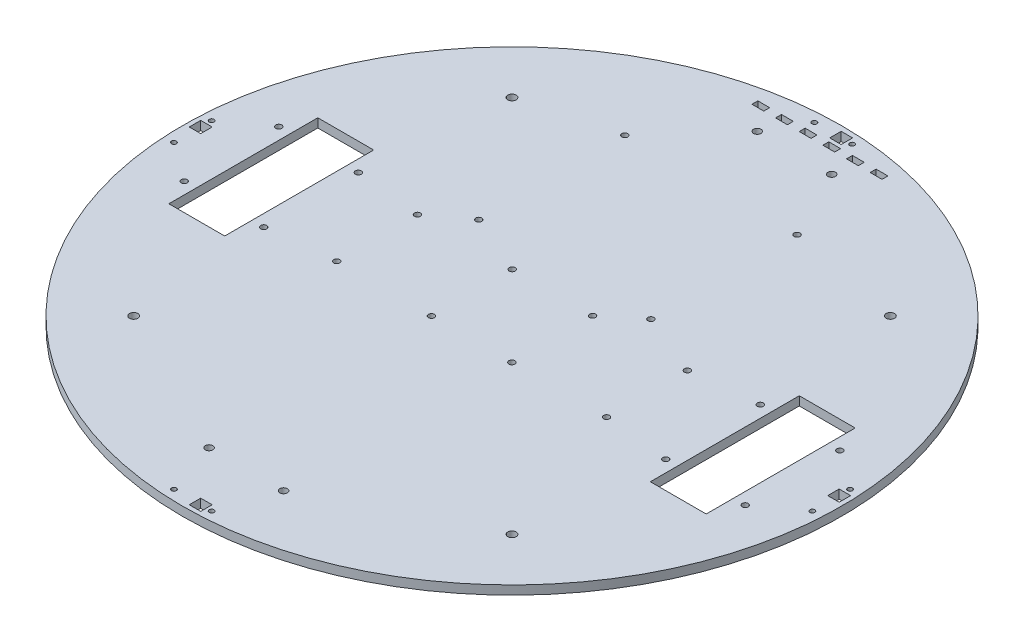
SolidWorks part; units mm, degrees
ref_plane "Front Plane" through (0, 0, 0) normal (0, 0, 1) x (1, 0, 0)
ref_plane "Top Plane" through (0, 0, 0) normal (0, 1, 0) x (1, 0, 0)
ref_plane "Right Plane" through (0, 0, 0) normal (1, 0, 0) x (0, 0, -1)
sketch "Sketch1" plane through (0, 0, 0) normal (0, 1, 0) x (1, 0, 0)
  line L0 (168.375, 7.335) -> (174.525, 7.335)
  line L1 (-144.3, 40) -> (-114.3, 40)
  line L2 (-144.3, 40) -> (-144.3, -40)
  line L3 (-144.3, -40) -> (-114.3, -40)
  line L4 (-114.3, 40) -> (-114.3, -40)
  line L13 (114.3, 40) -> (144.3, 40)
  line L14 (114.3, 40) -> (114.3, -40)
  line L15 (114.3, -40) -> (144.3, -40)
  line L16 (144.3, 40) -> (144.3, -40)
  line L17 (1.185, -168.375) -> (7.335, -168.375)
  line L18 (1.185, -168.375) -> (1.185, -174.525)
  line L19 (1.185, -174.525) -> (7.335, -174.525)
  line L20 (7.335, -168.375) -> (7.335, -174.525)
  line L21 (168.375, 7.335) -> (168.375, 1.185)
  line L22 (168.375, 1.185) -> (174.525, 1.185)
  line L23 (174.525, 7.335) -> (174.525, 1.185)
  line L24 (-174.525, 7.335) -> (-168.375, 7.335)
  line L25 (-174.525, 7.335) -> (-174.525, 1.185)
  line L26 (-174.525, 1.185) -> (-168.375, 1.185)
  line L27 (-168.375, 7.335) -> (-168.375, 1.185)
  line L28 (-21.295, 162.8645) -> (-14.945, 162.8645)
  line L29 (-33.995, 166.0395) -> (-27.645, 166.0395)
  line L30 (-33.995, 166.0395) -> (-33.995, 162.8645)
  line L31 (-33.995, 162.8645) -> (-27.645, 162.8645)
  line L32 (-27.645, 166.0395) -> (-27.645, 162.8645)
  line L33 (-14.945, 166.0395) -> (-14.945, 162.8645)
  line L34 (-21.295, 166.0395) -> (-14.945, 166.0395)
  line L35 (-21.295, 166.0395) -> (-21.295, 162.8645)
  line L36 (-8.595, 162.8645) -> (-2.245, 162.8645)
  line L37 (-2.245, 166.0395) -> (-2.245, 162.8645)
  line L38 (-8.595, 166.0395) -> (-2.245, 166.0395)
  line L39 (-8.595, 166.0395) -> (-8.595, 162.8645)
  line L40 (4.105, 162.8645) -> (10.455, 162.8645)
  line L41 (10.455, 166.0395) -> (10.455, 162.8645)
  line L42 (4.105, 166.0395) -> (10.455, 166.0395)
  line L43 (4.105, 166.0395) -> (4.105, 162.8645)
  line L44 (16.805, 162.8645) -> (23.155, 162.8645)
  line L45 (23.155, 166.0395) -> (23.155, 162.8645)
  line L46 (16.805, 166.0395) -> (23.155, 166.0395)
  line L47 (16.805, 166.0395) -> (16.805, 162.8645)
  line L48 (29.505, 162.8645) -> (35.855, 162.8645)
  line L49 (35.855, 166.0395) -> (35.855, 162.8645)
  line L50 (29.505, 166.0395) -> (35.855, 166.0395)
  line L51 (29.505, 166.0395) -> (29.505, 162.8645)
  circle A0 centre (0, 0) radius 177
  circle A1 centre (-150.65, 25.4) radius 1.6
  circle A2 centre (-150.65, -25.4) radius 1.6
  circle A3 centre (150.65, 25.4) radius 1.6
  circle A4 centre (150.65, -25.4) radius 1.6
  circle A5 centre (-107.95, 25.4) radius 1.6
  circle A6 centre (-107.95, -25.4) radius 1.6
  circle A7 centre (107.95, 25.4) radius 1.6
  circle A8 centre (107.95, -25.4) radius 1.6
  circle A9 centre (-53.7, 114.3) radius 1.6
  circle A10 centre (38.8, 114.3) radius 1.6
  circle A11 centre (-53.7, 35.8) radius 1.6
  circle A12 centre (38.8, 35.8) radius 1.6
  circle A13 centre (-101.6, -101.6) radius 2.2479
  circle A14 centre (101.6, -101.6) radius 2.2479
  circle A15 centre (-101.6, 101.6) radius 2.2479
  circle A16 centre (101.6, 101.6) radius 2.2479
  circle A17 centre (-20, -142.687) radius 2
  circle A18 centre (20, -142.687) radius 2
  circle A19 centre (-20, 151.7193) radius 2
  circle A20 centre (20, 151.7193) radius 2
  circle A21 centre (-10.125, -171.45) radius 1.3
  circle A22 centre (10.125, -171.45) radius 1.3
  circle A23 centre (171.45, -10.125) radius 1.3
  circle A24 centre (171.45, 10.125) radius 1.3
  circle A25 centre (-171.45, -10.125) radius 1.3
  circle A26 centre (-171.45, 10.125) radius 1.3
  point P9 (-114.3, 0)
  point P10 (-0.9618, 0)
  point P11 (-0.9618, 0)
  point P14 (114.3, 0)
  point P26 (-144.3, 0)
  point P27 (144.3, 0)
  dimension "D1" = 354
  dimension "D10" = 3.2
  dimension "D12" = 6.35
  dimension "D13" = 3.2
  dimension "D16" = 6.35
  dimension "D17" = 50.8
  dimension "D20" = 3.2
  dimension "D22" = 3.2
  dimension "D23" = 6.35
  dimension "D24" = 50.8
  dimension "D25" = 25.4
  dimension "D26" = 3.2
  dimension "D27" = 3.2
  dimension "D32" = 3.2
  dimension "D33" = 3.2
  dimension "D34" = 3.2
  dimension "D35" = 3.2
  dimension "D44" = 4.4958
  dimension "D45" = 4.4958
  dimension "D46" = 4.4958
  dimension "D47" = 4.4958
  dimension "D55" = 4
  dimension "D56" = 4
  dimension "D59" = 20
  dimension "D60" = 4
  dimension "D61" = 4
  dimension "D62" = 0
  dimension "D63" = 40
  dimension "D64" = 20
  dimension "D65" = 2.6
  dimension "D66" = 2.6
  dimension "D74" = 171.45
  dimension "D75" = 2.6
  dimension "D76" = 2.6
  dimension "D77" = 0
  dimension "D87" = 2.6
  dimension "D88" = 2.6
  dimension "D90" = 2.79
  dimension "D92" = 0
  dimension "D122" = 3.2
  dimension "D123" = 3.2
  dimension "D2" = 30
  dimension "D3" = 80
  dimension "D4" = 0
  dimension "D5" = 114.3
  dimension "D6" = 30
  dimension "D7" = 80
  dimension "D8" = 0
  dimension "D9" = 114.3
  dimension "D11" = 50.8
  dimension "D14" = 6.35
  dimension "D15" = 25.4
  dimension "D18" = 25.4
  dimension "D19" = 6.35
  dimension "D21" = 6.35
  dimension "D28" = 50.8
  dimension "D29" = 6.35
  dimension "D30" = 6.35
  dimension "D31" = 25.4
  dimension "D36" = 78.5
  dimension "D37" = 78.5
  dimension "D38" = 92.5
  dimension "D39" = 92.5
  dimension "D40" = 0
  dimension "D41" = 0
  dimension "D42" = 38.8
  dimension "D43" = 114.3
  dimension "D48" = 203.2
  dimension "D49" = 203.2
  dimension "D50" = 203.2
  dimension "D51" = 203.2
  dimension "D52" = 0
  dimension "D53" = 101.6
  dimension "D54" = 101.6
  dimension "D57" = 40
  dimension "D58" = 0
  dimension "D67" = 0
  dimension "D68" = 20.25
  dimension "D69" = 10.125
  dimension "D70" = 6.15
  dimension "D71" = 6.15
  dimension "D72" = 2.79
  dimension "D73" = 3.075
  dimension "D78" = 20.25
  dimension "D79" = 10.125
  dimension "D80" = 6.15
  dimension "D81" = 6.15
  dimension "D82" = 2.79
  dimension "D83" = 3.075
  dimension "D84" = 171.45
  dimension "D85" = 6.15
  dimension "D86" = 6.15
  dimension "D89" = 20.25
  dimension "D91" = 3.075
  dimension "D93" = 171.45
  dimension "D94" = 10.125
  dimension "D95" = 3.175
  dimension "D96" = 6.35
  dimension "D97" = 6
extrude "Boss-Extrude1" add sketch "Sketch1" along normal blind 4.7625
sketch "Sketch2" plane through (0, 4.7625, 0) normal (0, 1, 0) x (1, 0, 0)
  circle A4 centre (21.59, 21.69) radius 1.6
  circle A5 centre (21.59, -21.69) radius 1.6
  circle A6 centre (72.47, -21.69) radius 1.6
  circle A7 centre (72.47, 21.69) radius 1.6
  circle A12 centre (-72.47, 21.69) radius 1.6
  circle A13 centre (-72.47, -21.69) radius 1.6
  circle A14 centre (-21.59, -21.69) radius 1.6
  circle A15 centre (-21.59, 21.69) radius 1.6
  dimension "D3" = 3.2
  dimension "D4" = 3.2
  dimension "D5" = 3.2
  dimension "D6" = 3.2
  dimension "D7" = 3.2
  dimension "D8" = 3.2
  dimension "D9" = 3.2
  dimension "D10" = 3.2
  dimension "D11" = 50.88
  dimension "D12" = 50.88
  dimension "D13" = 0
  dimension "D14" = 0
  dimension "D22" = 21.69
  dimension "D26" = 21.59
  dimension "D15" = 43.38
  dimension "D16" = 50.88
  dimension "D17" = 50.88
  dimension "D18" = 0
  dimension "D19" = 0
  dimension "D20" = 43.38
  dimension "D21" = 0
  dimension "D23" = 0
  dimension "D24" = 21.69
  dimension "D25" = 21.59
extrude "Cut-Extrude1" cut sketch "Sketch2" against normal through all
sketch "Sketch3" plane through (0, 4.7625, 0) normal (0, 1, 0) x (1, 0, 0)
  line L0 (2.54, 174.244) -> (8.69, 174.244)
  line L1 (2.54, 174.244) -> (2.54, 168.094)
  line L2 (2.54, 168.094) -> (8.69, 168.094)
  line L3 (8.69, 174.244) -> (8.69, 168.094)
  circle A0 centre (-8.77, 171.169) radius 1.3
  circle A1 centre (11.48, 171.169) radius 1.3
  dimension "D1" = 2.6
  dimension "D2" = 2.6
  dimension "D3" = 0
  dimension "D4" = 20.25
  dimension "D5" = 6.15
  dimension "D6" = 6.15
  dimension "D7" = 2.79
  dimension "D8" = 3.075
  dimension "D9" = 2.54
  dimension "D10" = 174.244
extrude "Cut-Extrude2" cut sketch "Sketch3" against normal through all
